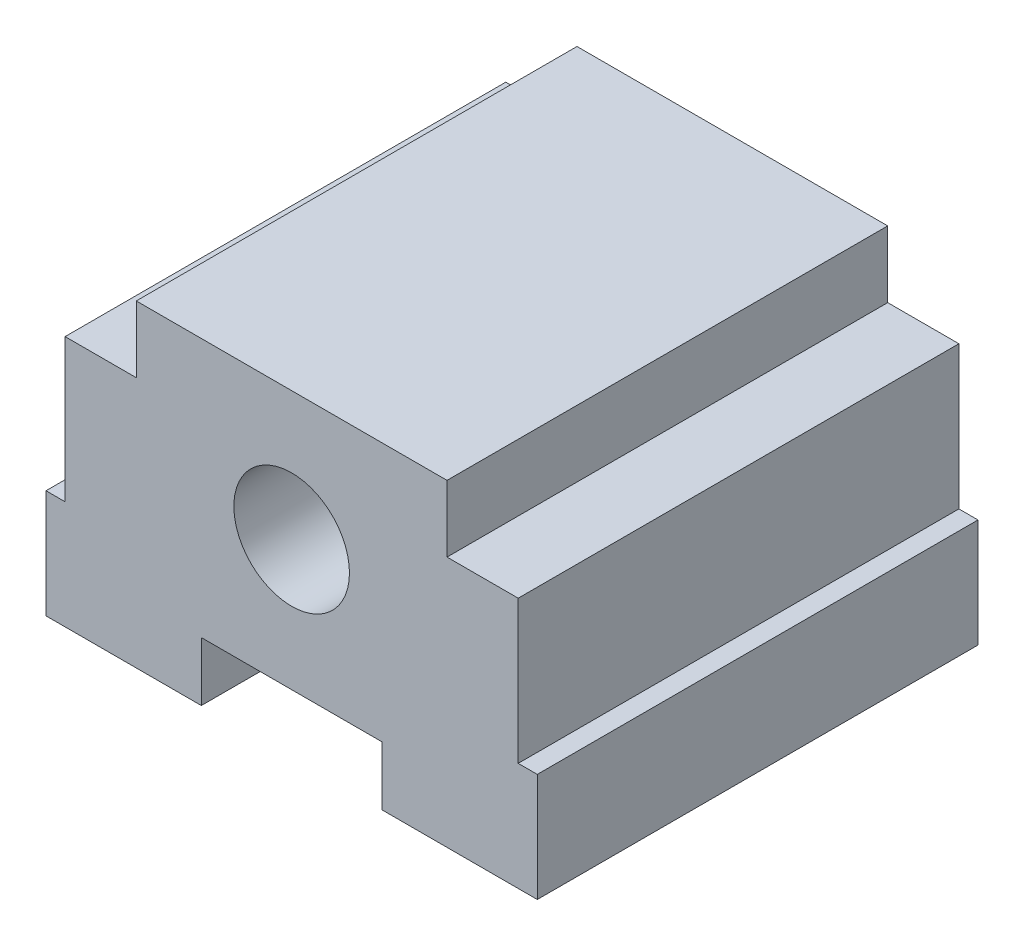
SolidWorks part; units mm, degrees
ref_plane "Front Plane" through (0, 0, 0) normal (0, 0, 1) x (1, 0, 0)
ref_plane "Top Plane" through (0, 0, 0) normal (0, 1, 0) x (1, 0, 0)
ref_plane "Right Plane" through (0, 0, 0) normal (1, 0, 0) x (0, 0, -1)
sketch "Sketch1" plane through (0, 0, 0) normal (0, 0, 1) x (1, 0, 0)
  line L0 (6.25, 0) -> (-6.25, 0)
  line L1 (-6.25, 0) -> (-6.25, -4.076)
  line L2 (-6.25, -4.076) -> (-17, -4.076)
  line L3 (-17, -4.076) -> (-17, 3.424)
  line L4 (-17, 3.424) -> (-15.6784, 3.424)
  line L5 (-15.6784, 3.424) -> (-15.6784, 13.324)
  line L6 (-15.6784, 13.324) -> (-10.7527, 13.324)
  line L7 (-10.7527, 13.324) -> (-10.7527, 17.924)
  line L8 (-10.7527, 17.924) -> (10.7527, 17.924)
  line L9 (0, -55) -> (0, 55) construction
  line L10 (10.7527, 13.324) -> (10.7527, 17.924)
  line L11 (15.6784, 13.324) -> (10.7527, 13.324)
  line L12 (15.6784, 3.424) -> (15.6784, 13.324)
  line L13 (17, 3.424) -> (15.6784, 3.424)
  line L14 (17, -4.076) -> (17, 3.424)
  line L15 (6.25, -4.076) -> (17, -4.076)
  line L16 (6.25, 0) -> (6.25, -4.076)
  point P3 (0, 0)
  point P12 (0, 0)
  point P16 (0, 17.924)
  point P23 (0, 0)
  dimension "D1" = 17
  dimension "D2" = 22
  dimension "D3" = 17.4
  dimension "D4" = 6.25
  dimension "D5" = 7.5
extrude "Boss-Extrude1" add sketch "Sketch1" along normal blind 30.5
sketch "Sketch2" plane through (0, 0, 30.5) normal (0, 0, 1) x (1, 0, 0)
  line L0 (0, 0) -> (0, 8.9984) construction
  circle A0 centre (0, 8.9984) radius 4
extrude "Cut-Extrude1" cut sketch "Sketch2" against normal blind 30.5
